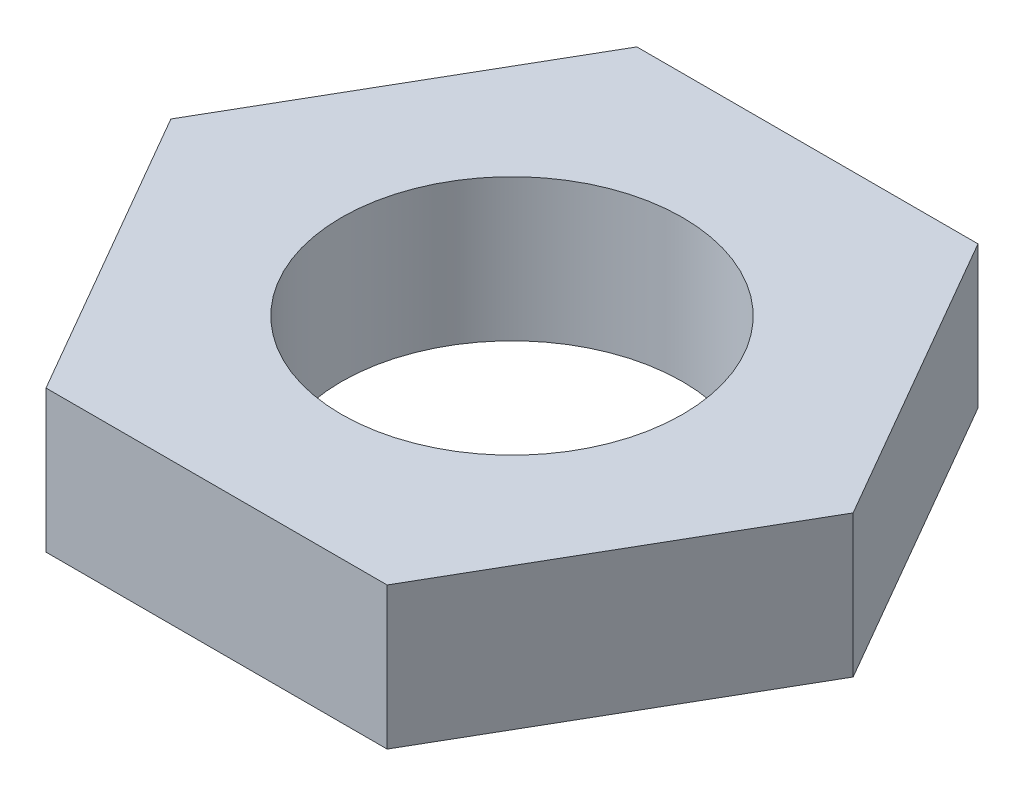
SolidWorks part; units mm, degrees
ref_plane "Front Plane" through (0, 0, 0) normal (0, 0, 1) x (1, 0, 0)
ref_plane "Top Plane" through (0, 0, 0) normal (0, 1, 0) x (1, 0, 0)
ref_plane "Right Plane" through (0, 0, 0) normal (1, 0, 0) x (0, 0, -1)
sketch "Sketch1" plane through (0, 0, 0) normal (0, 1, 0) x (1, 0, 0)
  line L1 (12, -20.7846) -> (24, 0)
  line L2 (24, 0) -> (12, 20.7846)
  line L3 (12, 20.7846) -> (-12, 20.7846)
  line L4 (-12, 20.7846) -> (-24, 0)
  line L5 (-24, 0) -> (-12, -20.7846)
  line L6 (-12, -20.7846) -> (12, -20.7846)
  circle A0 centre (0, 0) radius 20.7846 construction
  circle A1 centre (0, 0) radius 12
  point P10 (-12, -20.7846)
  dimension "D1" = 24
  dimension "D2" = 24
extrude "Boss-Extrude1" add sketch "Sketch1" along normal blind 10
